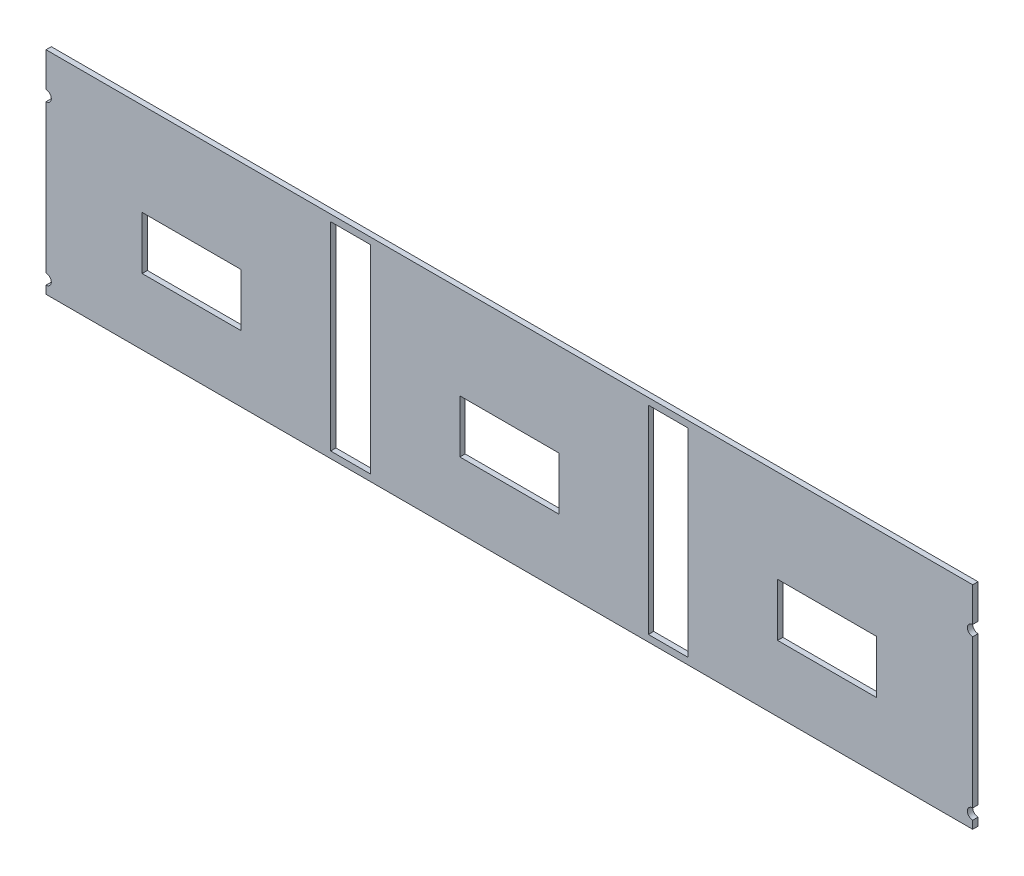
SolidWorks part; units mm, degrees
ref_plane "Front Plane" through (0, 0, 0) normal (0, 0, 1) x (1, 0, 0)
ref_plane "Top Plane" through (0, 0, 0) normal (0, 1, 0) x (1, 0, 0)
ref_plane "Right Plane" through (0, 0, 0) normal (1, 0, 0) x (0, 0, -1)
sketch "Sketch1" plane through (0, 0, 0) normal (0, 0, 1) x (1, 0, 0)
  line L0 (-216.4589, 99.8095) -> (-216.4589, -91.1144)
  line L1 (-368.8589, 81.3703) -> (88.3411, 81.3703)
  line L2 (-368.8589, 81.3703) -> (-368.8589, -20.2297)
  line L3 (-368.8589, -20.2297) -> (88.3411, -20.2297)
  line L4 (88.3411, 81.3703) -> (88.3411, -20.2297)
  line L5 (-316.4079, 36.8517) -> (-268.9099, 36.8517)
  line L6 (-316.4079, 36.8517) -> (-316.4079, 11.4517)
  line L7 (-316.4079, 11.4517) -> (-268.9099, 11.4517)
  line L8 (-268.9099, 36.8517) -> (-268.9099, 11.4517)
  line L9 (-164.0079, 36.8517) -> (-116.5099, 36.8517)
  line L10 (-164.0079, 36.8517) -> (-164.0079, 11.4517)
  line L11 (-164.0079, 11.4517) -> (-116.5099, 11.4517)
  line L12 (-116.5099, 36.8517) -> (-116.5099, 11.4517)
  line L13 (-11.6079, 36.8517) -> (35.8901, 36.8517)
  line L14 (-11.6079, 36.8517) -> (-11.6079, 11.4517)
  line L15 (-11.6079, 11.4517) -> (35.8901, 11.4517)
  line L16 (35.8901, 36.8517) -> (35.8901, 11.4517)
  line L18 (-362.5089, 111.3538) -> (-362.5089, -103.5467)
  line L20 (81.9911, 111.3538) -> (81.9911, -103.5467)
  line L21 (-64.0589, 99.8095) -> (-64.0589, -81.3462)
  line L22 (-292.6589, 45.6404) -> (-292.6589, -4.9767)
  line L23 (-140.2589, 45.6404) -> (-140.2589, -4.9767)
  line L24 (12.1411, 45.6404) -> (12.1411, -4.9767)
  line L26 (-225.9839, 78.1953) -> (-206.9339, 78.1953)
  line L27 (-225.9839, 78.1953) -> (-225.9839, -17.0547)
  line L28 (-225.9839, -17.0547) -> (-206.9339, -17.0547)
  line L29 (-206.9339, 78.1953) -> (-206.9339, -17.0547)
  line L30 (-73.5839, 78.1953) -> (-54.5339, 78.1953)
  line L31 (-73.5839, 78.1953) -> (-73.5839, -17.0547)
  line L32 (-73.5839, -17.0547) -> (-54.5339, -17.0547)
  line L33 (-54.5339, 78.1953) -> (-54.5339, -17.0547)
  circle A0 centre (-362.5089, 62.3203) radius 2.54
  circle A1 centre (-362.5089, -13.8797) radius 2.54
  circle A2 centre (81.9911, 62.3203) radius 2.54
  circle A3 centre (81.9911, -13.8797) radius 2.54
  dimension "D3" = 5.08
  dimension "D4" = 5.08
  dimension "D5" = 5.08
  dimension "D6" = 5.08
  dimension "D1" = 101.6
  dimension "D2" = 457.2
  dimension "D7" = 19.05
  dimension "D8" = 6.35
  dimension "D9" = 6.35
  dimension "D10" = 6.35
  dimension "D11" = 6.35
  dimension "D12" = 6.35
  dimension "D13" = 6.35
  dimension "D14" = 19.05
  dimension "D15" = 25.4
  dimension "D16" = 25.4
  dimension "D17" = 25.4
  dimension "D18" = 47.498
  dimension "D19" = 47.498
  dimension "D20" = 47.498
  dimension "D21" = 152.4
  dimension "D22" = 6.35
  dimension "D23" = 152.4
  dimension "D24" = 444.5
  dimension "D25" = 23.749
  dimension "D26" = 23.749
  dimension "D27" = 23.749
  dimension "D28" = 76.2
  dimension "D29" = 76.2
  dimension "D30" = 76.2
  dimension "D31" = 31.6814
  dimension "D32" = 19.05
  dimension "D33" = 95.25
  dimension "D34" = 3.175
  dimension "D35" = 9.525
  dimension "D36" = 95.25
  dimension "D37" = 19.05
  dimension "D38" = 9.525
  dimension "D39" = 3.175
extrude "Boss-Extrude2" add sketch "Sketch1" along normal blind 2.54
